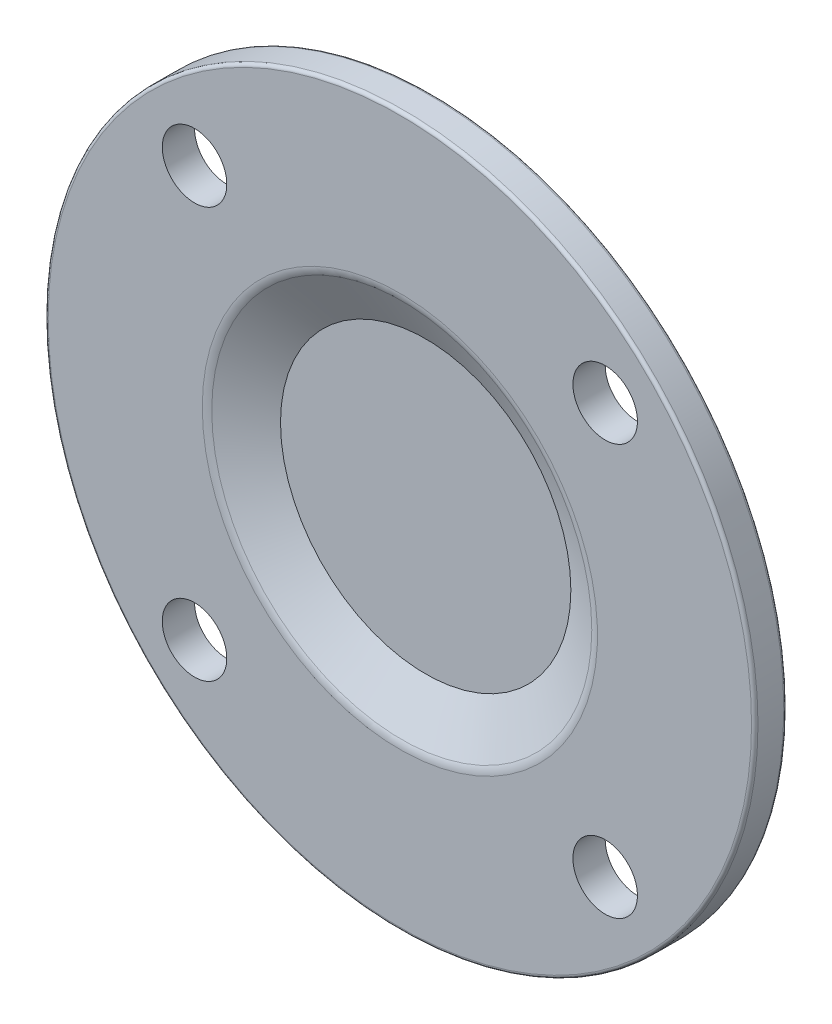
SolidWorks part; units mm, degrees
material "201 Annealed Stainless Steel (SS)"
ref_plane "Front Plane" through (0, 0, 0) normal (0, 0, 1) x (1, 0, 0)
ref_plane "Top Plane" through (0, 0, 0) normal (0, 1, 0) x (1, 0, 0)
ref_plane "Right Plane" through (0, 0, 0) normal (1, 0, 0) x (0, 0, -1)
sketch "Sketch1" plane through (0, 0, 0) normal (1, 0, 0) x (0, 0, -1)
  line L0 (0, 0) -> (0, 11) construction
  line L1 (0, 11) -> (0, 6)
  line L2 (1, 11) -> (1, 6)
  line L3 (1.8, 0) -> (1.8, 4.5)
  line L4 (1, 6) -> (1.8, 6) construction
  line L5 (1, 6) -> (1, 0) construction
  line L6 (1, 0) -> (1.8, 0) construction
  line L7 (1.8, 6) -> (1.8, 0) construction
  line L8 (0.8, 0) -> (0.8, 4.5)
  line L9 (0.8, 0) -> (1.8, 0)
  line L10 (0, 11) -> (1, 11)
  line L11 (0, 6) -> (0.8, 4.5)
  line L12 (1, 6) -> (1.8, 4.5)
  line L13 (0, 0) -> (9.085, 0) construction
  dimension "D1" = 11
  dimension "D2" = 5
  dimension "D4" = 1.8
  dimension "D5" = 4.5
  dimension "D3" = 1
  dimension "D6" = 1
revolve "Revolve1" add sketch "Sketch1" angle 360 about L13
fillet "Fillet1" radius 0.5 3 edges at (6, 0, 0) (6, 0, -1) (4.5, 0, -1.8)
sketch "Sketch2" plane through (0, 0, -1) normal (0, 0, -1) x (-1, 0, 0)
  line L0 (0, 0) -> (6.364, 6.364) construction
  circle A0 centre (0, 0) radius 9 construction
  circle A1 centre (6.364, 6.364) radius 1
  circle A2 centre (6.364, -6.364) radius 1
  circle A3 centre (-6.364, -6.364) radius 1
  circle A4 centre (-6.364, 6.364) radius 1
  point P13 (0, 0)
  dimension "D1" = 18
  dimension "D2" = 2
  dimension "D3" = 4
extrude "Cut-Extrude1" cut sketch "Sketch2" against normal through all
fillet "Fillet2" radius 0.1 2 edges at (11, 0, 0) (11, 0, -1)
